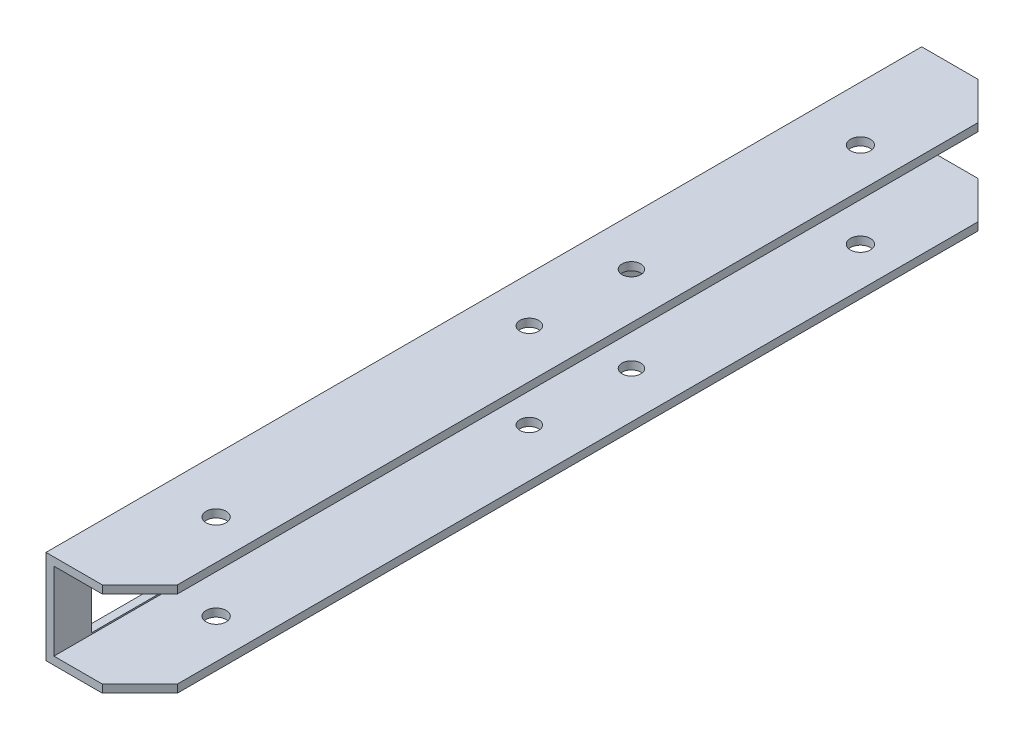
SolidWorks part; units mm, degrees
ref_plane "Front Plane" through (0, 0, 0) normal (0, 0, 1) x (1, 0, 0)
ref_plane "Top Plane" through (0, 0, 0) normal (0, 1, 0) x (1, 0, 0)
ref_plane "Right Plane" through (0, 0, 0) normal (1, 0, 0) x (0, 0, -1)
sketch "Sketch1" plane through (0, 0, 0) normal (0, 0, 1) x (1, 0, 0)
  line L0 (0, -37.5) -> (0, 37.5)
  line L1 (0, 37.5) -> (75, 37.5)
  line L2 (75, 37.5) -> (75, 31.15)
  line L3 (75, 31.15) -> (6.35, 31.15)
  line L4 (6.35, 31.15) -> (6.35, -31.15)
  line L5 (6.35, -31.15) -> (75, -31.15)
  line L6 (75, -31.15) -> (75, -37.5)
  line L7 (75, -37.5) -> (0, -37.5)
  line L8 (0, 0) -> (6.35, 0) construction
  dimension "D1" = 75
  dimension "D2" = 75
  dimension "D3" = 6.35
extrude "Boss-Extrude1" add sketch "Sketch1" along normal blind 700
sketch "Sketch3" plane through (0, 0, 0) normal (-1, 0, 0) x (0, 0, 1)
  line L0 (30, -30) -> (155, -30)
  line L1 (30, -30) -> (30, 30)
  line L2 (155, -30) -> (155, 30)
  line L3 (30, 30) -> (155, 30)
  line L4 (30, -30) -> (155, 30) construction
  line L5 (155, -30) -> (30, 30) construction
  line L6 (350, -37.5) -> (350, 96.3047) construction
  line L7 (700, -37.5) -> (0, -37.5) construction
  line L8 (0, 0) -> (92.5, 0) construction
  line L9 (670, -30) -> (545, -30)
  line L10 (545, -30) -> (545, 30)
  line L11 (670, 30) -> (545, 30)
  line L12 (670, -30) -> (670, 30)
  line L13 (700, 37.5) -> (700, -37.5) construction
  line L14 (400, 10.3833) -> (373, 10.3833)
  line L15 (400, 10.3833) -> (400, -10.3833)
  line L16 (300, 10.3833) -> (300, -10.3833) construction
  line L17 (400, -10.3833) -> (393, -10.3833)
  line L18 (400, 10.3833) -> (300, -10.3833) construction
  line L19 (300, 10.3833) -> (400, -10.3833) construction
  line L20 (307, 10.3833) -> (300, 10.3833)
  line L21 (373, -10.3833) -> (373, -31.15) construction
  line L22 (373, -31.15) -> (327, -31.15)
  line L23 (327, -31.15) -> (327, -10.3833)
  line L24 (373, 31.15) -> (327, 31.15)
  line L25 (373, 31.15) -> (373, 10.3833)
  line L26 (327, 31.15) -> (327, 10.3833) construction
  line L27 (700, -31.15) -> (0, -31.15) construction
  line L28 (373, 31.15) -> (327, 10.3833) construction
  line L29 (327, 31.15) -> (373, 10.3833) construction
  line L30 (327, 31.15) -> (307, 31.15)
  line L31 (327, -10.3833) -> (300, -10.3833)
  line L32 (300, 10.3833) -> (270, 10.3833)
  line L33 (270, 10.3833) -> (270, -10.3833)
  line L34 (270, -10.3833) -> (300, -10.3833)
  line L35 (700, 31.15) -> (0, 31.15) construction
  line L36 (307, 31.15) -> (307, 10.3833)
  line L37 (373, -31.15) -> (393, -31.15)
  line L38 (393, -31.15) -> (393, -10.3833)
  point P1 (92.5, 0)
  point P19 (350, 0)
  point P28 (350, 20.7667)
  dimension "D1" = 60
  dimension "D2" = 30
  dimension "D3" = 125
  dimension "D4" = 20
  dimension "D5" = 100
  dimension "D6" = 46
  dimension "D9" = 30
extrude "Cut-Extrude1" cut sketch "Sketch3" against normal through all
chamfer "Chamfer1" distance 30 angle 45 4 edges at (75, 34.325, 700) (75, -34.325, 700) (75, -34.325, 0) (75, 34.325, 0)
sketch "Sketch4" plane through (0, 37.5, 0) normal (0, 1, 0) x (1, 0, 0)
  line L0 (75, -607.5) -> (43.5, -607.5) construction
  line L1 (75, -670) -> (75, -30) construction
  line L2 (0, -670) -> (0, -545) construction
  line L4 (0, -549.5) -> (0, -665.5) construction
  line L5 (0, -700) -> (0, 0) construction
  line L6 (0, -607.5) -> (43.5, -607.5) construction
  line L7 (0, -350) -> (49.4239, -350) construction
  circle A0 centre (43.5, -607.5) radius 8
  circle A1 centre (43.5, -607.5) radius 62.5 construction
  circle A2 centre (43.5, -607.5) radius 72.5 construction
  circle A3 centre (43.5, -92.5) radius 8
  dimension "D1" = 16
  dimension "D2" = 125
  dimension "D3" = 145
  dimension "D4" = 116
  dimension "D5" = 31.5
extrude "Cut-Extrude2" cut sketch "Sketch4" against normal through all
sketch "Sketch5" plane through (0, -37.5, 0) normal (0, -1, 0) x (1, 0, 0)
  line L1 (0, 350) -> (36.323, 350) construction
  line L6 (75, 670) -> (75, 30) construction
  line L7 (43.5, 607.5) -> (36.323, 350) construction
  line L8 (36.323, 350) -> (43.5, 92.5) construction
  line L11 (0, 700) -> (0, 0) construction
  circle A0 centre (38, 270.0176) radius 7.5
  circle A2 centre (36.323, 350) radius 7.5
  point P10 (43.5, 92.5)
  point P11 (43.5, 607.5)
  dimension "D1" = 15
  dimension "D2" = 37
  dimension "D3" = 80
  dimension "D4" = 36.323
  dimension "D5" = 257.6
extrude "Cut-Extrude3" cut sketch "Sketch5" against normal through all
chamfer "Chamfer2" distance 3 angle 45 7 edges at (0, -20.7667, 393) (0, 20.7667, 307) (6.35, 0, 270) (6.35, 20.7667, 373) (6.35, -20.7667, 327) (6.35, 0, 545) (6.35, 0, 155)
fillet "Fillet1" radius 3 8 edges at (1.675, 31.15, 373) (3.175, 10.3833, 400) (3.175, -10.3833, 400) (1.675, -31.15, 327) (1.675, -10.3833, 270) (1.675, 10.3833, 270) (4.675, -31.15, 393) (4.675, 31.15, 307)
